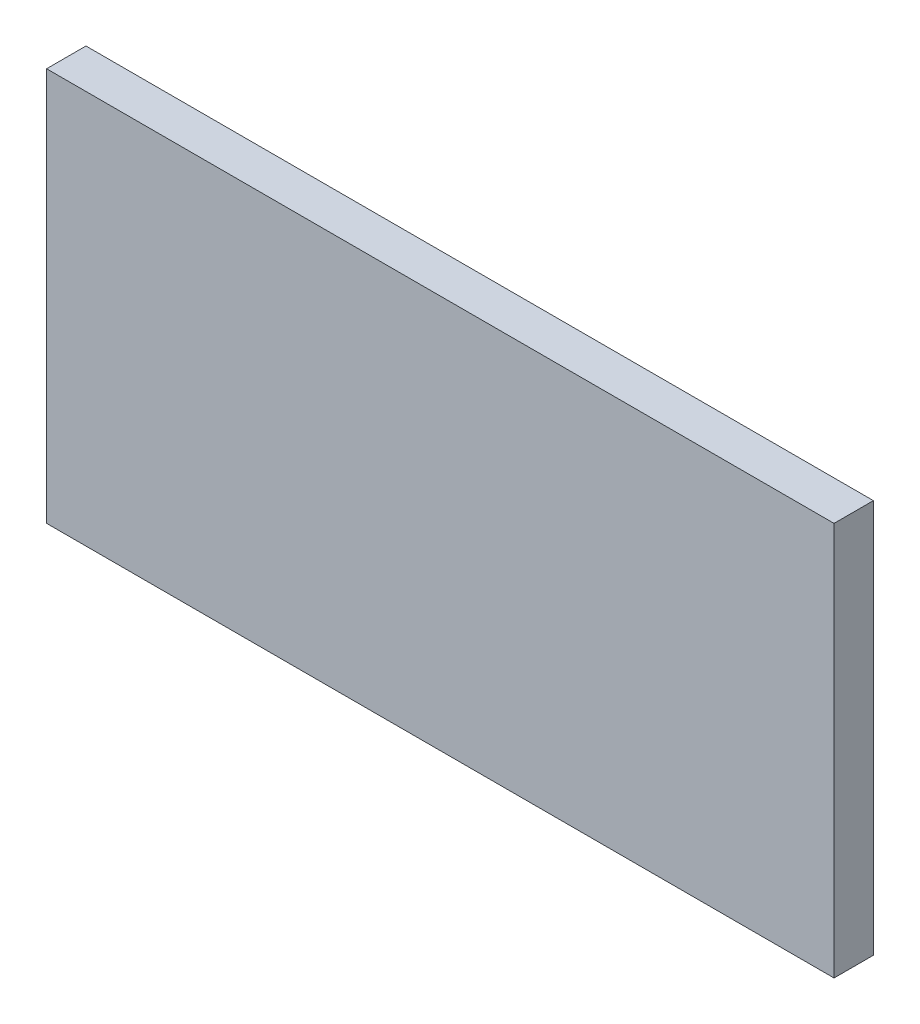
SolidWorks part; units mm, degrees
ref_plane "Front Plane" through (0, 0, 0) normal (0, 0, 1) x (1, 0, 0)
ref_plane "Top Plane" through (0, 0, 0) normal (0, 1, 0) x (1, 0, 0)
ref_plane "Right Plane" through (0, 0, 0) normal (1, 0, 0) x (0, 0, -1)
sketch "Sketch1" plane through (0, 0, 0) normal (0, 0, 1) x (1, 0, 0)
  line L1 (-50, 25) -> (50, 25)
  line L2 (-50, 25) -> (-50, -25)
  line L3 (-50, -25) -> (50, -25)
  line L4 (50, 25) -> (50, -25)
  point P0 (0, 0)
  point P5 (0, 0)
  point P7 (0, 0)
  dimension "D1" = 100
  dimension "D2" = 50
  dimension "D3" = 25
  dimension "D4" = 50
extrude "Boss-Extrude1" add sketch "Sketch1" along normal blind 5
